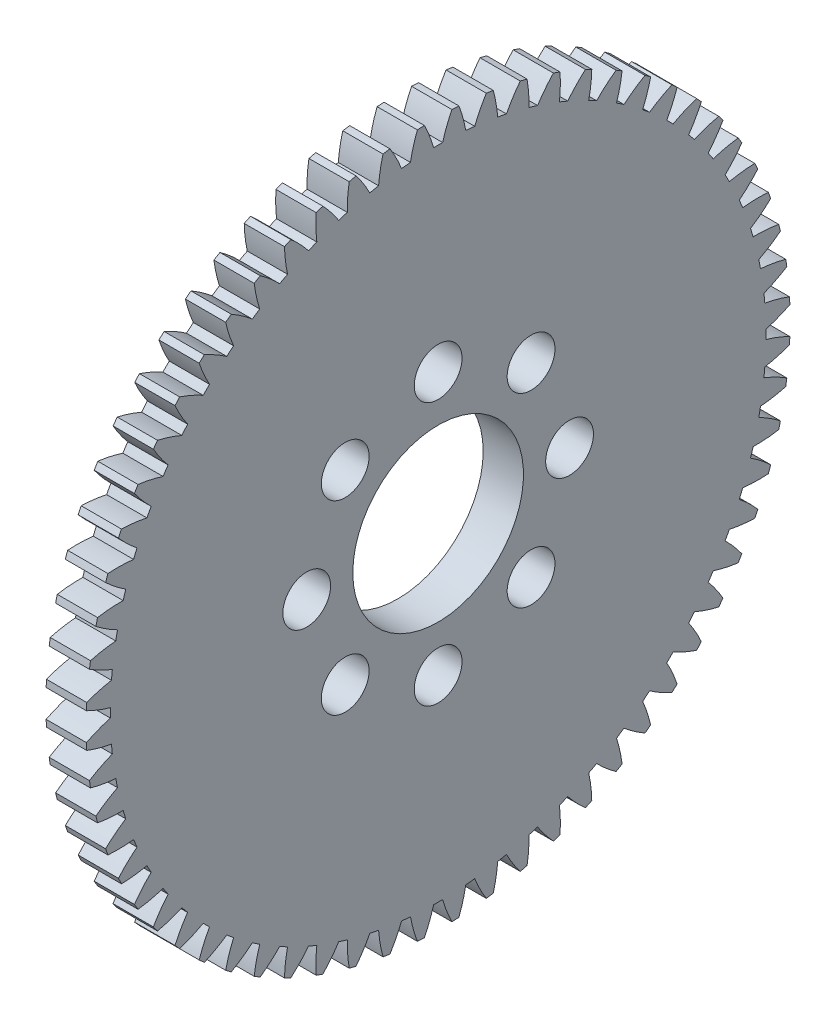
SolidWorks part; units mm, degrees
ref_plane "Plane1" through (0, 0, 0) normal (0, 0, 1) x (1, 0, 0)
ref_plane "Plane2" through (0, 0, 0) normal (0, 1, 0) x (1, 0, 0)
ref_plane "Plane3" through (0, 0, 0) normal (1, 0, 0) x (0, 0, -1)
other "Configuration Table"
sketch "HoldingSke" plane through (0, 0, 0) normal (0, 1, 0) x (1, 0, 0)
  line L0 (0, 0) -> (356.3081, -730.5398)
  line L1 (-15, 0) -> (100, 0) construction
  line L2 (0, 0) -> (-2.1039, 2.3779)
  line L3 (0, 0) -> (-11.863, 4.5341)
  line L4 (0, 0) -> (3.7858, 7.762)
  line L5 (0, 0) -> (-47.5972, -17.7524)
  line L6 (0, 0) -> (-2.4846, -1.6763)
  line L7 (-2.1039, 2.3779) -> (8.8308, 51.9871)
  line L8 (-76.2, 54.61) -> (-61.976, 54.61)
  line L9 (-71.009, 38.7566) -> (-53.1078, 45.2721)
  line L10 (-76.2, 71.12) -> (104.1128, 71.12)
  line L11 (0, 0) -> (-2.9972, 0)
  line L12 (-76.2, 101.6) -> (-76.1716, 101.6)
  line L13 (24.9733, 27.94) -> (52.9518, 28.4284)
  line L14 (24.9733, 27.94) -> (25.0241, 27.9398)
  line L15 (24.9733, 27.94) -> (100.4021, 29.52)
  circle A0 centre (0, 0) radius 6.35
  circle A1 centre (0, 0) radius 24.3967
  circle A2 centre (0, 0) radius 38.1
  circle A3 centre (0, 0) radius 6.35
  dimension "MHD" = 48.7934
  dimension "Hub_dia" = 76.2
  dimension "Bore" = 12.7
  dimension "MBD" = 12.7
  dimension "Num_teeth" = 64
  dimension "Pitch" = 812.8
  dimension "Overall_len" = 50.8
  dimension "Show_teeth" = 64
  dimension "Thickness" = 2.9972
  dimension "OAL" = 50.8001
  dimension "T_dim" = 14.224
  dimension "Ap" = 20
  dimension "H" = 19.05
  dimension "Pitch_radius" = 180.3128
  dimension "Width" = 2.9972
  dimension "Backlash" = 0.0284
  dimension "Addendum_fac" = 1
  dimension "Dedendum_fac" = 1.2
  dimension "Clearance_fac" = 0.2
  dimension "Dedendum_add" = 0.0508
sketch "BasProSke" plane through (0, 0, 0) normal (0, 1, 0) x (1, 0, 0)
  line L0 (-10, 0) -> (60, 0) construction
  line L1 (0, 0) -> (0, 26.1937)
  line L2 (0, 0) -> (2.9972, 0)
  line L3 (2.9972, 0) -> (2.9972, 26.1937)
  line L4 (2.9972, 26.1937) -> (0, 26.1937)
  dimension "Thickness" = 2.9972
  dimension "Diameter" = 52.3875
revolve "Base-Revolve" add sketch "BasProSke" angle 360 about L0
sketch "TooCutSke" plane through (0, 0, 0) normal (1, 0, 0) x (0, 0, -1)
  line L1 (0, 0) -> (0, 107) construction
  line L2 (0, 0) -> (-0.6731, 25.3911) construction
  line L3 (0, 0) -> (-2.492, 50.7259) construction
  line L4 (-0.6731, 25.3911) -> (-1.246, 25.3629) construction
  arc A0 (0.3337, 24.3944) -> (-0.3337, 24.3944) centre (0, 0) ccw
  arc A1 (1.0373, 26.1986) -> (-1.0373, 26.1986) centre (0, 0) ccw
  circle A2 centre (0, 0) radius 25.4 construction
  circle A3 centre (0, 0) radius 23.8682 construction
  arc A4 (-0.3337, 24.3944) -> (-1.0373, 26.1986) centre (-10.1082, 21.6221) ccw
  arc A5 (1.0373, 26.1986) -> (0.3337, 24.3944) centre (10.1082, 21.6221) ccw
  dimension "Root_dia" = 48.7934
  dimension "Overcut_dia" = 52.4383
  dimension "Pitch_dia" = 50.8
  dimension "Base_dia" = 47.7364
  dimension "Flank_rad" = 10.16
  dimension "Half_ang" = 2.813
  dimension "Half_CT" = 0.5736
extrude "ToothCut" cut sketch "TooCutSke" along normal through all
fillet "Breaks" [suppressed] radius 0.0159
fillet "RootFillets" [suppressed] radius 0.2095
pattern_circular "TeethCuts" count 64 every 5.625 about axis through (-10, 0, 0) along (1, 0, 0) of "ToothCut", "RootFillets", "Breaks"
sketch "HubNeaOneSke" plane through (0, 0, 0) normal (-1, 0, 0) x (0, 0, 1)
  circle A0 centre (0, 0) radius 24.3967
  dimension "Diameter" = 48.7934
extrude "HubNearOne" [suppressed] add sketch "HubNeaOneSke" along normal blind 47.8029
sketch "HubNeaBotSke" plane through (0, 0, 0) normal (-1, 0, 0) x (0, 0, 1)
  circle A0 centre (0, 0) radius 24.3967
  dimension "Diameter" = 48.7934
extrude "HubNearBoth" [suppressed] add sketch "HubNeaBotSke" along normal blind 23.9014
ref_plane "FarPln" through (2.9972, 0, 0) normal (1, 0, 0) x (0, 0, -1)
sketch "HubFarSke" plane through (2.9972, 0, 0) normal (1, 0, 0) x (0, 0, -1)
  circle A0 centre (0, 0) radius 24.3967
  dimension "Diameter" = 48.7934
extrude "HubFar" [suppressed] add sketch "HubFarSke" along normal blind 23.9014
sketch "BorSke" plane through (0, 0, 0) normal (1, 0, 0) x (0, 0, -1)
  circle A0 centre (0, 0) radius 6.35
  dimension "Diameter" = 12.7
extrude "Bore" cut sketch "BorSke" along normal mid plane 101.6001
sketch "KeySke" plane through (0, 0, 0) normal (1, 0, 0) x (0, 0, -1)
  line L0 (-1.5875, 0) -> (-1.5875, 7.874)
  line L1 (-1.5875, 7.874) -> (1.5875, 7.874)
  line L2 (1.5875, 7.874) -> (1.5875, 0)
  line L3 (0, 0) -> (0, 34) construction
  line L4 (-1.5875, 0) -> (1.5875, 0)
  dimension "Offset" = 7.874
  dimension "Width" = 3.175
extrude "Keyway" [suppressed] cut sketch "KeySke" along normal mid plane 101.6001
pattern_circular "Keyway2" [suppressed] count 2 every 90 about axis through (-10, 0, 0) along (1, 0, 0)
sketch "Sketch1" plane through (2.9972, 0, 0) normal (1, 0, 0) x (0, 0, -1)
  circle A0 centre (0, 0) radius 9.779 construction
  circle A1 centre (0, 9.779) radius 1.778
  circle A2 centre (6.9148, 6.9148) radius 1.778
  circle A3 centre (9.779, 0) radius 1.778
  circle A4 centre (6.9148, -6.9148) radius 1.778
  circle A5 centre (0, -9.779) radius 1.778
  circle A6 centre (-6.9148, -6.9148) radius 1.778
  circle A7 centre (-9.779, 0) radius 1.778
  circle A8 centre (-6.9148, 6.9148) radius 1.778
  point P21 (0, 0)
  dimension "D1" = 19.558
  dimension "D2" = 3.556
  dimension "D4" = 3.556
  dimension "D3" = 8
extrude "Cut-Extrude1" cut sketch "Sketch1" against normal through all
equation "' \"Pitch@HoldingSke\" = 4"
equation "' \"Num_teeth@HoldingSke\" = 12"
equation "' \"Ap@HoldingSke\" =  20"
equation "' \"Ap@HoldingSke\" = 20"
equation "' \"Width@HoldingSke\" = 0.5"
equation "' \"Hub_dia@HoldingSke\"= 1"
equation "' \"Hub_dia@HoldingSke\" = 1"
equation "' \"Overall_len@HoldingSke\" = 1.0"
equation "' \"Bore@HoldingSke\" = 0.75"
equation "' \"T_dim@HoldingSke\" = 0.85"
equation "' \"Width@KeySke\" = 0.25"
equation "' \"Show_teeth@HoldingSke\" = 13"
equation "' \"Backlash@HoldingSke\" = 0.009"
equation "' \"Addendum_fac@HoldingSke\" = 1.0"
equation "' \"Dedendum_fac@HoldingSke\" = 1.25"
equation "' \"Dedendum_add@HoldingSke\" = 0.00005"
equation "' \"Clearance_fac@HoldingSke\" = 0.25"
equation "' \"Pitch@HoldingSke\" = 0.5"
equation "' \"Num_teeth@HoldingSke\" = 23"
equation "' \"Show_teeth@HoldingSke\" = 23"
equation "' \"Backlash@HoldingSke\" = 0.0375"
equation "\"Overcut_dia@TooCutSke\" = (\"Num_teeth@HoldingSke\" + 2 * \"Addendum_fac@HoldingSke\") / \"Pitch@HoldingSke\" + 0.002"
equation "\"Pitch_dia@TooCutSke\" = \"Num_teeth@HoldingSke\" / \"Pitch@HoldingSke\""
equation "\"Base_dia@TooCutSke\" = \"Num_teeth@HoldingSke\" / \"Pitch@HoldingSke\" * cos((\"Ap@HoldingSke\"  * 3.14159265 / 180))"
equation "\"Root_dia@TooCutSke\" = (\"Num_teeth@HoldingSke\" + 2) / \"Pitch@HoldingSke\" - 2 * (\"Addendum_fac@HoldingSke\" + \"Dedendum_fac@HoldingSke\") / \"Pitch@HoldingSke\" - \"Dedendum_add@HoldingSke\" * 2"
equation "\"Half_ang@TooCutSke\" = 180 / \"Num_teeth@HoldingSke\""
equation "\"Half_CT@TooCutSke\" = \"Num_teeth@HoldingSke\" / \"Pitch@HoldingSke\" * sin((3.14159265 / 2 / \"Num_teeth@HoldingSke\")) / 2 - 7 * \"Backlash@HoldingSke\" / 4"
equation "\"Flank_rad@TooCutSke\" = \"Num_teeth@HoldingSke\" / \"Pitch@HoldingSke\" / 5"
equation "\"Radius@RootFillets\" = \"Clearance_fac@HoldingSke\" / \"Pitch@HoldingSke\" + \"Dedendum_add@HoldingSke\""
equation "\"Break_rad@Breaks\" = 0.02 / \"Pitch@HoldingSke\""
equation "\"Thickness@HoldingSke\" = \"Width@HoldingSke\""
equation "\"OAL@HoldingSke\" = \"Thickness@HoldingSke\""
equation "\"MHD@HoldingSke\" = (\"Num_teeth@HoldingSke\" + 2) / \"Pitch@HoldingSke\" - 2 * (\"Addendum_fac@HoldingSke\" + \"Dedendum_fac@HoldingSke\")  / \"Pitch@HoldingSke\" - \"Dedendum_add@HoldingSke\" * 2"
equation "\"MBD@HoldingSke\" = (\"Num_teeth@HoldingSke\" + 2) / \"Pitch@HoldingSke\" - 2 * (\"Addendum_fac@HoldingSke\" + \"Dedendum_fac@HoldingSke\")  / \"Pitch@HoldingSke\" - \"Dedendum_add@HoldingSke\" * 2 - 0.002"
equation "\"MHD@HoldingSke\" = ((sgn( \"MHD@HoldingSke\" - \"Hub_dia@HoldingSke\" )-1)*( \"MHD@HoldingSke\" - \"Hub_dia@HoldingSke\" ))/-2+ \"Hub_dia@HoldingSke\""
equation "\"MBD@HoldingSke\" = ((sgn( \"MBD@HoldingSke\" - \"Bore@HoldingSke\" )-1)*( \"MBD@HoldingSke\" - \"Bore@HoldingSke\" ))/-2+ \"Bore@HoldingSke\""
equation "\"OAL@HoldingSke\" = ((sgn( \"OAL@HoldingSke\" - \"Overall_len@HoldingSke\" )+1)*( \"OAL@HoldingSke\" - \"Overall_len@HoldingSke\" ))/2 + \"Overall_len@HoldingSke\" + 0.000002"
equation "\"Num_teeth@TeethCuts\" = int( \"Show_teeth@HoldingSke\" ) + 1"
equation "\"Num_teeth@TeethCuts\" = ((sgn( \"Num_teeth@TeethCuts\" - \"Num_teeth@HoldingSke\" )-1)*( \"Num_teeth@TeethCuts\" - \"Num_teeth@HoldingSke\" ))/-2+ \"Num_teeth@HoldingSke\""
equation "\"Num_teeth@TeethCuts\" = ((sgn( \"Num_teeth@TeethCuts\" - 2.0)+1)*( \"Num_teeth@TeethCuts\" - 2.0))/2 +2.0"
equation "\"Angle@TeethCuts\" = 360.0 / \"Num_teeth@HoldingSke\""
equation "\"Diameter@BasProSke\" = (\"Num_teeth@HoldingSke\" + 2 * \"Addendum_fac@HoldingSke\") / \"Pitch@HoldingSke\""
equation "\"Thickness@BasProSke\"  = \"Thickness@HoldingSke\""
equation "' \"Fillet_rad@BasProSke\" =  \"Thickness@HoldingSke\" * 0.05"
equation "' \"Fillet_rad@BasProSke\" = \"Thickness@HoldingSke\" * 0.05"
equation "\"MHD@HoldingSke\" = ((sgn( \"MHD@HoldingSke\" - \"Root_dia@TooCutSke\" )-1)*( \"MHD@HoldingSke\" - \"Root_dia@TooCutSke\" ))/-2+ \"Root_dia@TooCutSke\""
equation "\"Diameter@HubNeaOneSke\" = \"MHD@HoldingSke\""
equation "\"Length@HubNearOne\" = \"OAL@HoldingSke\" - \"Thickness@BasProSke\""
equation "\"Diameter@HubNeaBotSke\" = \"MHD@HoldingSke\""
equation "\"Length@HubNearBoth\" = ( \"OAL@HoldingSke\" - \"Thickness@BasProSke\" ) / 2.0"
equation "\"Thickness@FarPln\" = \"Thickness@BasProSke\""
equation "\"Diameter@HubFarSke\" = \"MHD@HoldingSke\""
equation "\"Length@HubFar\" = ( \"OAL@HoldingSke\" - \"Thickness@BasProSke\" ) / 2.0"
equation "\"Diameter@BorSke\" = \"MBD@HoldingSke\""
equation "\"D1@Bore\" = \"OAL@HoldingSke\" * 2.0"
equation "\"D1@Keyway\" = \"OAL@HoldingSke\" * 2.0"
equation "\"Offset@KeySke\" = \"T_dim@HoldingSke\" - \"MBD@HoldingSke\" / 2.0"
